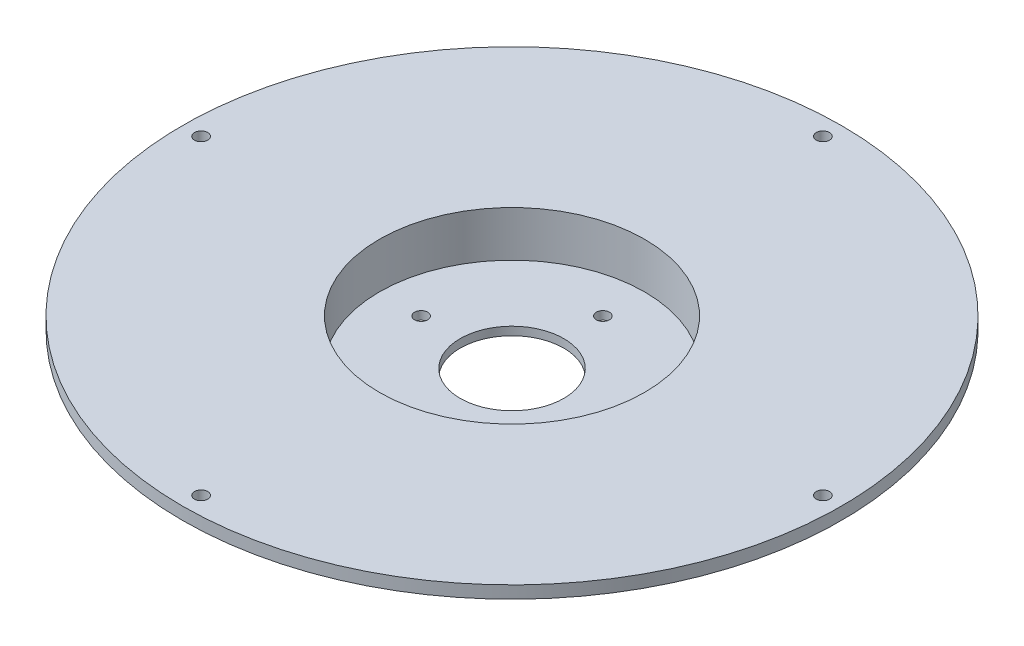
SolidWorks part; units mm, degrees
ref_plane "前视基准面" through (0, 0, 0) normal (0, 0, 1) x (1, 0, 0)
ref_plane "上视基准面" through (0, 0, 0) normal (0, 1, 0) x (1, 0, 0)
ref_plane "右视基准面" through (0, 0, 0) normal (1, 0, 0) x (0, 0, -1)
other "Configuration Table"
sketch "草图1" plane through (0, 0, 0) normal (0, 1, 0) x (1, 0, 0)
  line L0 (0, 75) -> (0, 0)
  line L1 (-75, 0) -> (0, 0)
  circle A0 centre (0, 0) radius 79.5
  circle A1 centre (0, 75) radius 1.6
  circle A2 centre (75, 0) radius 1.6
  circle A3 centre (0, -75) radius 1.6
  circle A4 centre (-75, 0) radius 1.6
  circle A5 centre (0, 21.92) radius 1.6
  circle A6 centre (21.92, 0) radius 1.6
  circle A7 centre (0, -21.92) radius 1.6
  circle A8 centre (-21.92, 0) radius 1.6
  point P14 (0, 0)
  point P23 (0, 0)
  dimension "D1" = 159
  dimension "D3" = 3.2
  dimension "D5" = 75
  dimension "D6" = 3.2
  dimension "D9" = 21.92
  dimension "D2" = 75
  dimension "D7" = 21.92
  dimension "D4" = 4
  dimension "D8" = 4
extrude "凸台-拉伸1" add sketch "草图1" along normal blind 3
sketch "草图5" plane through (0, 0, 0) normal (0, -1, 0) x (1, 0, 0)
  circle A0 centre (0, 0) radius 34
  dimension "D1" = 68
extrude "凸台-拉伸2" add sketch "草图5" along normal blind 10
sketch "草图7" plane through (0, 3, 0) normal (0, 1, 0) x (1, 0, 0)
  circle A0 centre (0, 21.92) radius 1.6
  circle A1 centre (21.92, 0) radius 1.6
  circle A2 centre (0, -21.92) radius 1.6
  circle A3 centre (-21.92, 0) radius 1.6
  dimension "D1" = 3.2
  dimension "D2" = 3.2
  dimension "D3" = 3.2
  dimension "D4" = 3.2
extrude "切除-拉伸1" cut sketch "草图7" against normal blind 22
sketch "草图8" plane through (0, 3, 0) normal (0, 1, 0) x (1, 0, 0)
  circle A0 centre (0, 0) radius 32
  dimension "D1" = 64
extrude "切除-拉伸2" cut sketch "草图8" against normal blind 11
sketch "草图10" plane through (0, -8, 0) normal (0, 1, 0) x (1, 0, 0)
  circle A0 centre (0, 0) radius 12.5
  dimension "D1" = 25
extrude "切除-拉伸3" cut sketch "草图10" against normal blind 12
